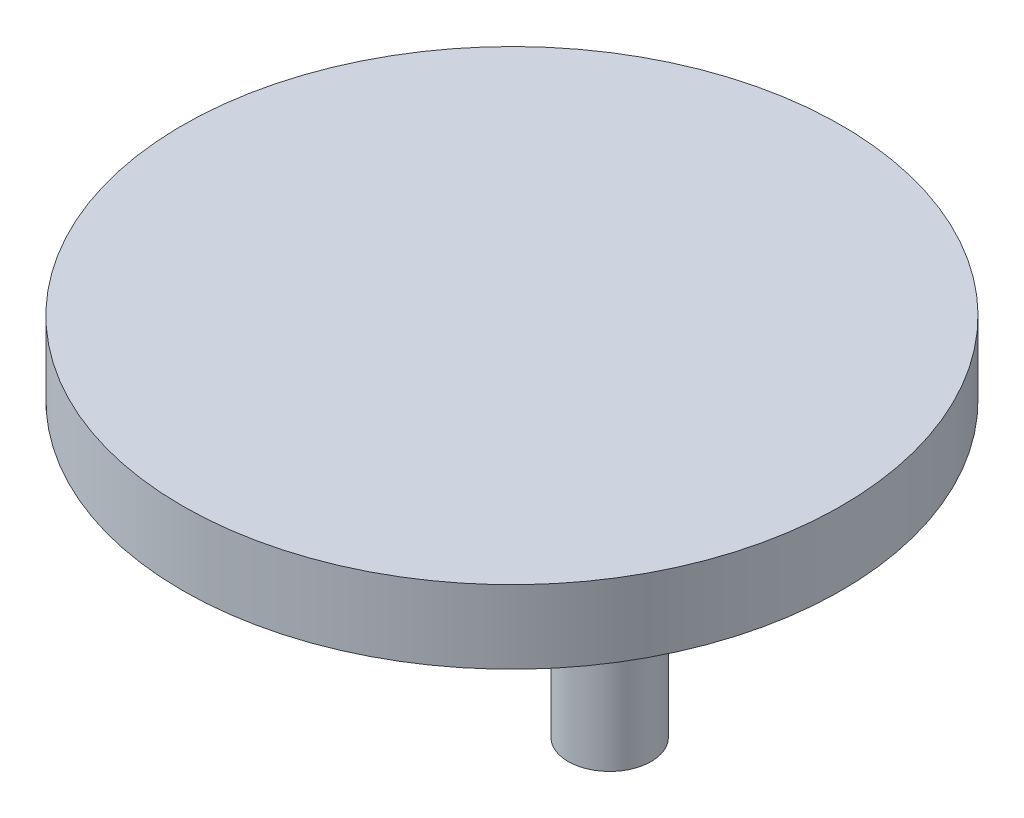
SolidWorks part; units mm, degrees
ref_plane "Front Plane" through (0, 0, 0) normal (0, 0, 1) x (1, 0, 0)
ref_plane "Top Plane" through (0, 0, 0) normal (0, 1, 0) x (1, 0, 0)
ref_plane "Right Plane" through (0, 0, 0) normal (1, 0, 0) x (0, 0, -1)
sketch "Sketch1" plane through (0, 0, 0) normal (0, 1, 0) x (1, 0, 0)
  line L0 (0, 0) -> (0, 21.875) construction
  circle A0 centre (0, 21.875) radius 3.4
  circle A1 centre (18.9443, -10.9375) radius 3.4
  circle A2 centre (-18.9443, -10.9375) radius 3.4
  point P11 (0, 0)
  dimension "D1" = 6.8
  dimension "D2" = 3
sketch "Sketch2" plane through (0, 0, 0) normal (0, 1, 0) x (1, 0, 0)
  circle A0 centre (0, 0) radius 27
  dimension "D1" = 54
extrude "Boss-Extrude1" add sketch "Sketch2" along normal blind 6
extrude "Boss-Extrude2" add sketch "Sketch1" against normal blind 9
chamfer "Chamfer1" distance 1 angle 45 3 edges at (-18.9443, 0, 14.3375) (0, 0, -18.475) (18.9443, 0, 14.3375)
